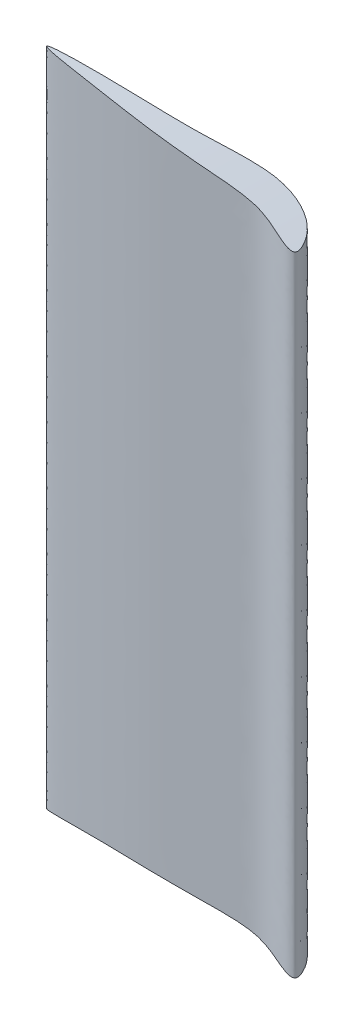
SolidWorks part; units mm, degrees
ref_plane "Plan de face" through (0, 0, 0) normal (0, 0, 1) x (1, 0, 0)
ref_plane "Plan de dessus" through (0, 0, 0) normal (0, 1, 0) x (1, 0, 0)
ref_plane "Plan de droite" through (0, 0, 0) normal (1, 0, 0) x (0, 0, -1)
sketch "Esquisse2" plane through (0, 0, 0) normal (0, 1, 0) x (1, 0, 0)
  line L1 (0, 0) -> (5, 0) construction
  line L2 (0, 0) -> (0, 1.5) construction
  line L3 (0, 1.5) -> (5, 1.5) construction
  line L4 (5, 0) -> (5, 1.5) construction
  spline S0 degree 3 poles (4.4016, 0.8385) (5.0793, 0.5916) (4.827, 1.3546) (4.13, 1.5672) (3.4696, 1.4431) (2.9564, 1.2967) (1.958, 0.9898) (-1.1348, 0.6519) (1.3334, 0.6097) (2.2516, 0.6357) (3.1282, 0.7387) (3.8765, 0.8872) (4.4016, 0.8385) (5.0793, 0.5916) (4.827, 1.3546) knots -0.181222 -0.102778 -0.050322 0 0.019678 0.137076 0.173086 0.216071 0.287021 0.51713 0.646238 0.741155 0.818778 0.897222 0.949678 1 1.019678 1.137076 1.173086 only from (5, 0.75) to (5, 0.75)
  dimension "D1" = 5
  dimension "D2" = 1.5
ref_plane "Plan3" through (0, 15.4, 0) normal (0, 1, 0) x (-1, 0, 0)
sketch "Esquisse3" plane through (0, 15.4, 0) normal (0, 1, 0) x (-1, 0, 0)
  line L0 (0, 0) -> (-5, 0) construction
  line L1 (0, 0) -> (0, -1.5) construction
  line L2 (0, -1.5) -> (-5, -1.5) construction
  line L3 (-5, 0) -> (-5, -1.5) construction
  spline S0 degree 3 poles (-4.4016, -0.8385) (-5.0793, -0.5916) (-4.827, -1.3546) (-4.13, -1.5672) (-3.4696, -1.4431) (-2.9564, -1.2967) (-1.958, -0.9898) (1.1348, -0.6519) (-1.3334, -0.6097) (-2.2516, -0.6357) (-3.1282, -0.7387) (-3.8765, -0.8872) (-4.4016, -0.8385) (-5.0793, -0.5916) (-4.827, -1.3546) knots -0.181222 -0.102778 -0.050322 0 0.019678 0.137076 0.173086 0.216071 0.287021 0.51713 0.646238 0.741155 0.818778 0.897222 0.949678 1 1.019678 1.137076 1.173086 only from (-5, -0.75) to (-5, -0.75)
  dimension "D1" = 5
  dimension "D2" = 1.5
sketch "Esquisse4" plane through (0, 0, 0) normal (1, 0, 0) x (0, 0, -1)
  line L0 (0.6747, 0) -> (0.6747, 15.4)
sweep "Balayage1" add profiles "Esquisse2" path "Esquisse4"
sketch "Esquisse6" plane through (0, 0, 0) normal (0, 0, 1) x (1, 0, 0)
  line L0 (-0.0177, 15.4) -> (-0.0177, 0) construction
  arc A0 (5.0028, 0) -> (-0.0177, 0.5089) centre (1.0781, -13.6989) ccw
  dimension "D1" = 14.25
extrude "Enlèv. mat.-Extru.1" cut sketch "Esquisse6" against normal through all and the other way through all
sketch "Esquisse7" plane through (0, 0, 0) normal (0, 0, 1) x (1, 0, 0)
  line L1 (0.686, 0) -> (-0.686, 0) construction
  arc A0 (5.7229, 12.5447) -> (-1.5452, 14.1) centre (-3.5601, -13.0754) ccw
  dimension "D1" = 27.25
  dimension "D2" = 14.1
extrude "Enlèv. mat.-Extru.2" cut sketch "Esquisse7" against normal through all and the other way through all flip side to cut
